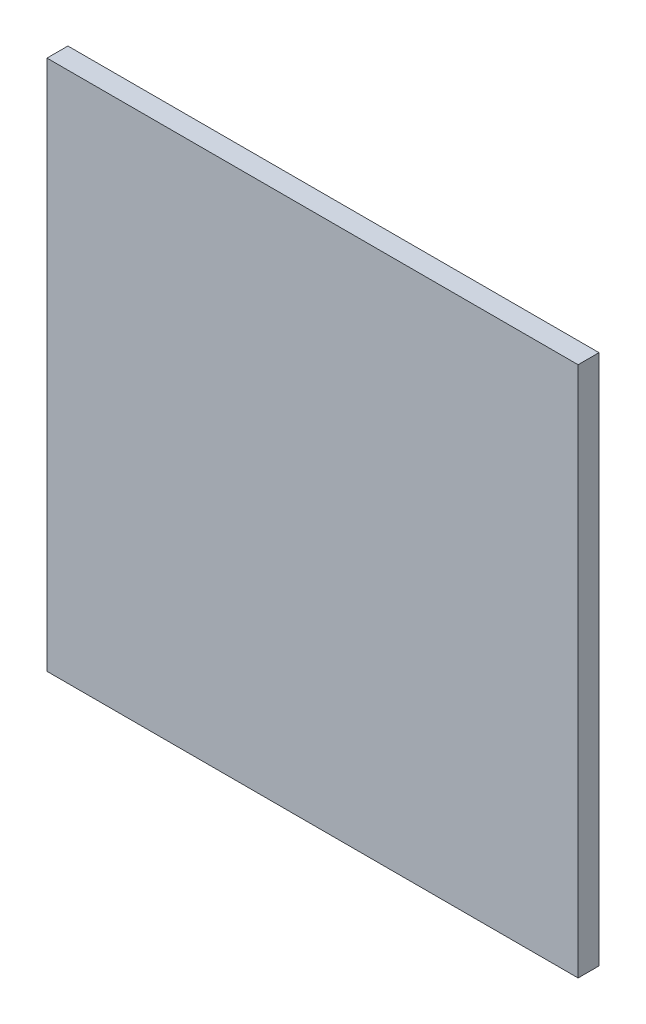
SolidWorks part; units mm, degrees
ref_plane "Front Plane" through (0, 0, 0) normal (0, 0, 1) x (1, 0, 0)
ref_plane "Top Plane" through (0, 0, 0) normal (0, 1, 0) x (1, 0, 0)
ref_plane "Right Plane" through (0, 0, 0) normal (1, 0, 0) x (0, 0, -1)
sketch "스케치1" plane through (0, 0, 0) normal (0, 0, 1) x (1, 0, 0)
  line L1 (-38.1, -38.1) -> (38.1, -38.1)
  line L2 (-38.1, -38.1) -> (-38.1, 38.1)
  line L3 (-38.1, 38.1) -> (38.1, 38.1)
  line L4 (38.1, -38.1) -> (38.1, 38.1)
  line L5 (-38.1, -38.1) -> (38.1, 38.1) construction
  line L6 (-38.1, 38.1) -> (38.1, -38.1) construction
  point P0 (0, 0)
  dimension "D1" = 76.2
  dimension "D2" = 76.2
extrude "보스-돌출1" add sketch "스케치1" along normal blind 3
sketch "스케치2" plane through (0, 0, 3) normal (0, 0, 1) x (1, 0, 0)
  line L0 (-2.0683, 70.0423) -> (141.9317, 70.0423) construction
